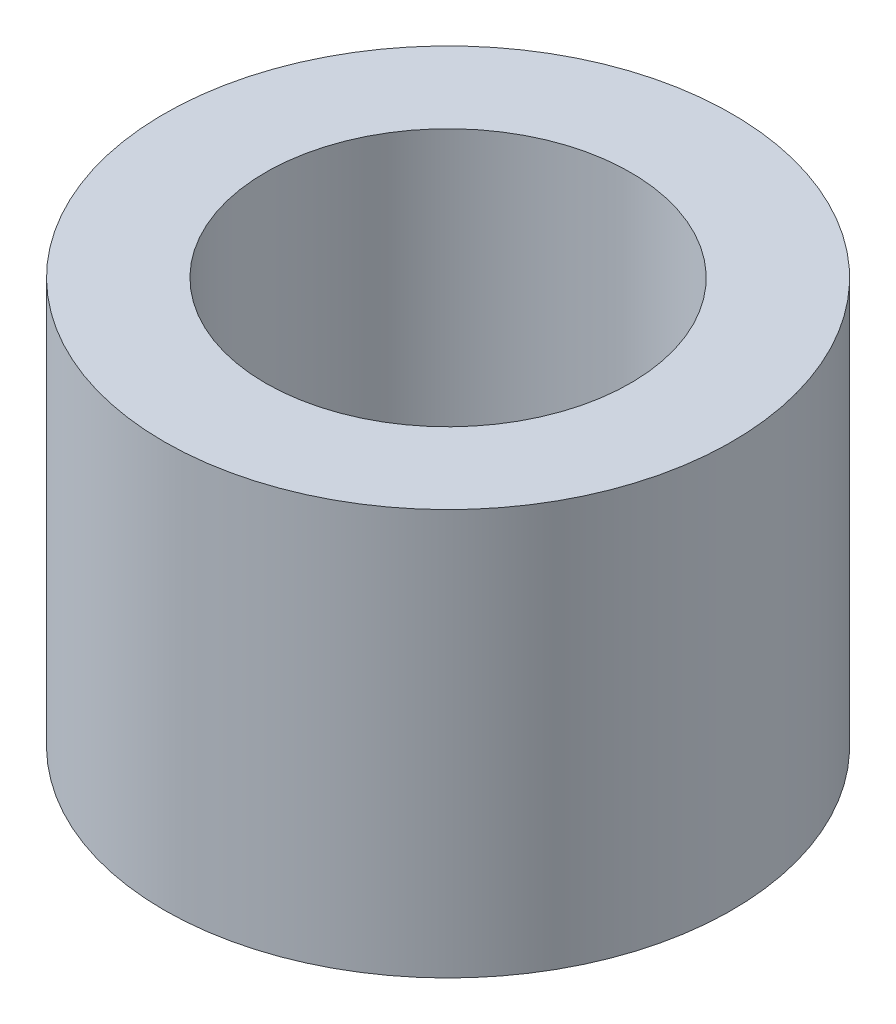
SolidWorks part; units mm, degrees
ref_plane "Front Plane" through (0, 0, 0) normal (0, 0, 1) x (1, 0, 0)
ref_plane "Top Plane" through (0, 0, 0) normal (0, 1, 0) x (1, 0, 0)
ref_plane "Right Plane" through (0, 0, 0) normal (1, 0, 0) x (0, 0, -1)
sketch "Sketch1" plane through (0, 0, 0) normal (0, 1, 0) x (1, 0, 0)
  circle A0 centre (0, 0) radius 3.5
  dimension "6" = 7
extrude "Boss-Extrude1" add sketch "Sketch1" along normal blind 5
sketch "Sketch4" plane through (0, 5, 0) normal (0, 1, 0) x (1, 0, 0)
  circle A0 centre (0, 0) radius 2.25
  dimension "D1" = 4.5
extrude "Cut-Extrude1" cut sketch "Sketch4" against normal through all
